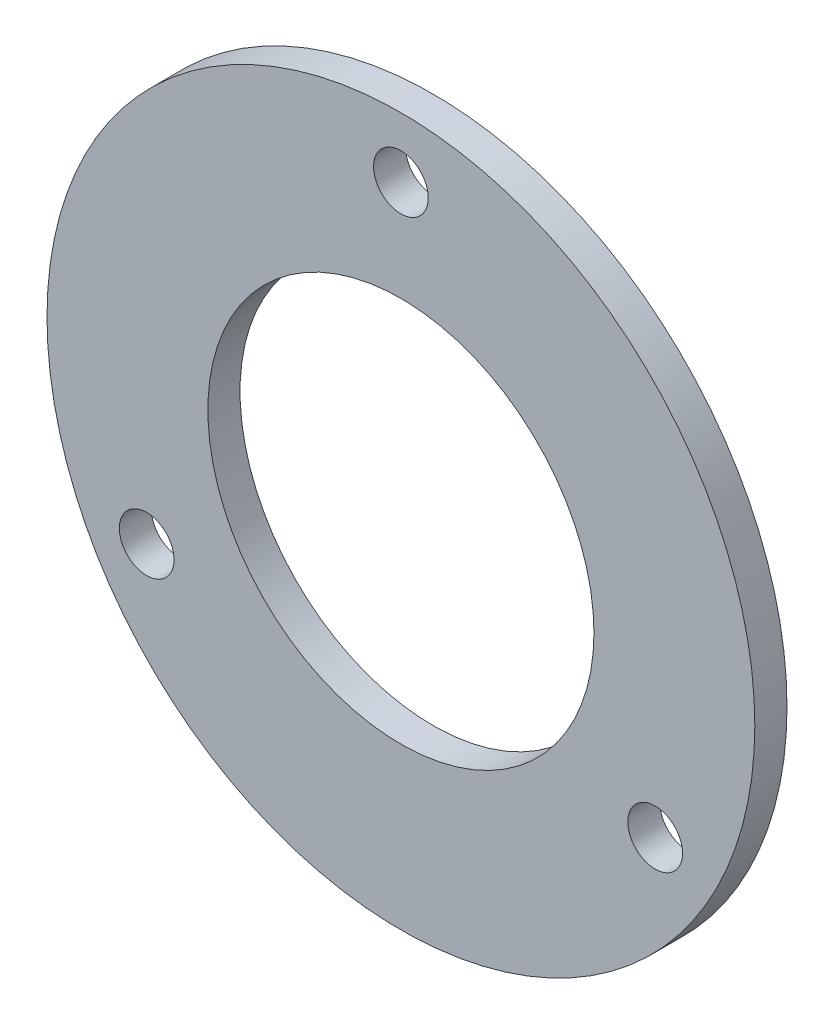
SolidWorks part; units mm, degrees
ref_plane "Front Plane" through (0, 0, 0) normal (0, 0, 1) x (1, 0, 0)
ref_plane "Top Plane" through (0, 0, 0) normal (0, 1, 0) x (1, 0, 0)
ref_plane "Right Plane" through (0, 0, 0) normal (1, 0, 0) x (0, 0, -1)
sketch "S01 - Outer race retaining lip" plane through (0, 0, 0) normal (0, 0, 1) x (1, 0, 0)
  circle A0 centre (0, 0) radius 22
  circle A1 centre (0, 0) radius 12
  dimension "D1" = 24
  dimension "D2" = 44
extrude "01 - Outer race retaining lip" add sketch "S01 - Outer race retaining lip" along normal blind 2
sketch "S02 - Three accessible screw holes" plane through (0, 0, 0) normal (0, 0, 1) x (1, 0, 0)
  circle A0 centre (0, 18.25) radius 1.7
  circle A1 centre (-15.805, -9.125) radius 1.7
  circle A2 centre (15.805, -9.125) radius 1.7
  dimension "D1" = 3.4
  dimension "D2" = 3.4
  dimension "D3" = 3.4
  dimension "D4" = 15.805
  dimension "D5" = 15.805
  dimension "D6" = 18.25
  dimension "D7" = 9.125
extrude "02 - Three accessible screw holes" cut sketch "S02 - Three accessible screw holes" along normal blind 4 from offset 1
